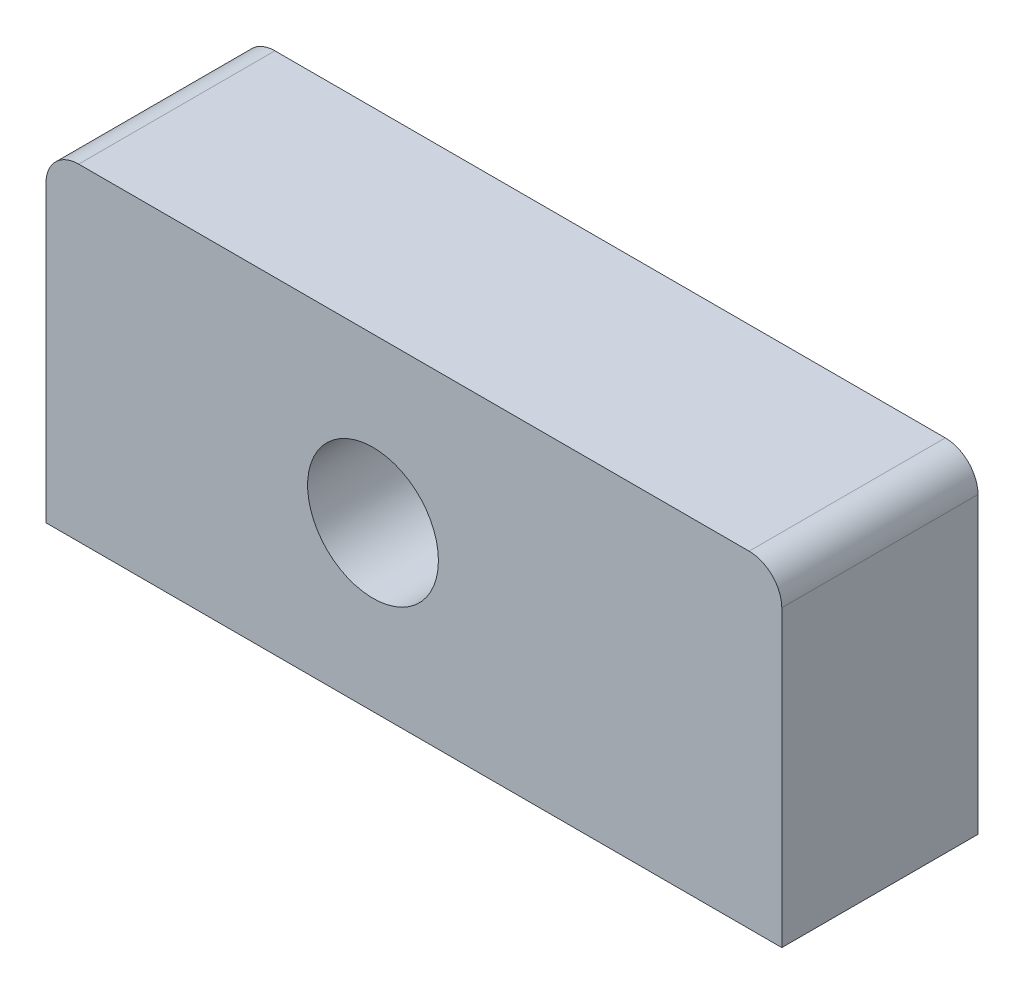
SolidWorks part; units mm, degrees
ref_plane "Front Plane" through (0, 0, 0) normal (0, 0, 1) x (1, 0, 0)
ref_plane "Top Plane" through (0, 0, 0) normal (0, 1, 0) x (1, 0, 0)
ref_plane "Right Plane" through (0, 0, 0) normal (1, 0, 0) x (0, 0, -1)
sketch "Sketch1" plane through (0, 0, 0) normal (0, 0, 1) x (1, 0, 0)
  line L0 (20, 20) -> (20, 0) construction
  line L1 (0, 0) -> (45, 0)
  line L2 (0, 0) -> (0, 20)
  line L3 (0, 20) -> (45, 20)
  line L4 (45, 0) -> (45, 20)
  line L5 (0, 10) -> (45, 10) construction
  circle A0 centre (20, 10) radius 4
  point P9 (20, 10)
  dimension "D3" = 8
  dimension "D1" = 20
  dimension "D2" = 45
  dimension "D4" = 20
extrude "Boss-Extrude1" add sketch "Sketch1" along normal blind 12
fillet "Fillet1" radius 2 2 edges at (45, 20, 6) (0, 20, 6)
